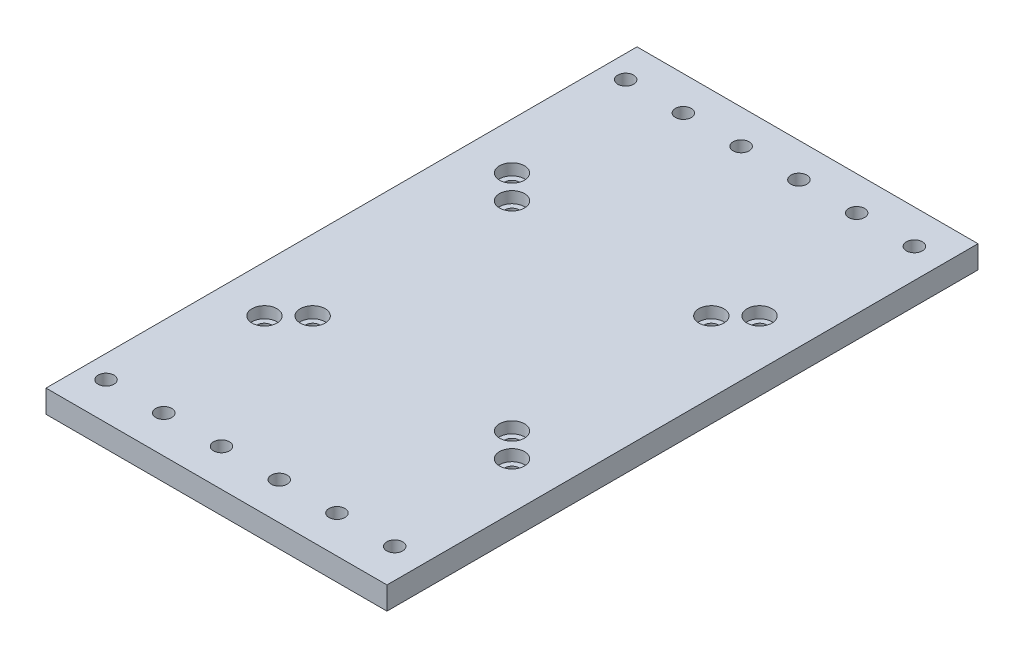
SolidWorks part; units mm, degrees
ref_plane "Front Plane" through (0, 0, 0) normal (0, 0, 1) x (1, 0, 0)
ref_plane "Top Plane" through (0, 0, 0) normal (0, 1, 0) x (1, 0, 0)
ref_plane "Right Plane" through (0, 0, 0) normal (1, 0, 0) x (0, 0, -1)
sketch "Sketch2" plane through (0, 0, 0) normal (0, 1, 0) x (1, 0, 0)
  line L1 (-75, -130) -> (75, -130)
  line L2 (-75, -130) -> (-75, 130)
  line L3 (-75, 130) -> (75, 130)
  line L4 (75, -130) -> (75, 130)
  line L5 (-75, -130) -> (75, 130) construction
  line L6 (-75, 130) -> (75, -130) construction
  point P0 (0, 0)
  dimension "D1" = 150
  dimension "D2" = 260
extrude "Boss-Extrude1" add sketch "Sketch2" along normal blind 10
sketch "Sketch3" plane through (0, 10, 0) normal (0, 1, 0) x (1, 0, 0)
  line L0 (-43.8406, -43.8406) -> (0, 0) construction
  line L1 (0, 0) -> (43.8406, 43.8406) construction
  line L2 (0, 0) -> (-14.158, -14.158) construction
  line L3 (-43.8406, 43.8406) -> (0, 0) construction
  line L4 (0, 0) -> (27.2687, 27.2687) construction
  line L5 (0, 0) -> (43.8406, -43.8406) construction
  line L6 (0, 0) -> (71.3814, -71.3814) construction
  line L7 (0, 0) -> (-73.7954, 73.7954) construction
  line L8 (-75, -130) -> (75, -130) construction
  circle A0 centre (-54.4472, -54.4472) radius 3.125
  circle A2 centre (-43.8406, -43.8406) radius 3.125
  circle A5 centre (54.4472, 54.4472) radius 3.125
  circle A6 centre (43.8406, 43.8406) radius 3.125
  circle A7 centre (-54.4472, 54.4472) radius 3.125
  circle A8 centre (-43.8406, 43.8406) radius 3.125
  circle A9 centre (54.4472, -54.4472) radius 3.125
  circle A10 centre (43.8406, -43.8406) radius 3.125
  point P21 (0, 0)
  point P25 (27.2687, 27.2687)
  dimension "D1" = 6.25
  dimension "D2" = 15
  dimension "D3" = 124
  dimension "D5" = 6.25
  dimension "D6" = 15
  dimension "D4" = 15
  dimension "D7" = 124
  dimension "D8" = 15
  dimension "D9" = 45
extrude "Cut-Extrude1" cut sketch "Sketch3" against normal through all
sketch "Sketch4" plane through (0, 10, 0) normal (0, 1, 0) x (1, 0, 0)
  circle A0 centre (-43.8406, -43.8406) radius 5.5
  circle A1 centre (-54.4472, -54.4472) radius 5.5
  circle A2 centre (43.8406, -43.8406) radius 5.5
  circle A3 centre (54.4472, -54.4472) radius 5.5
  circle A4 centre (43.8406, 43.8406) radius 5.5
  circle A5 centre (54.4472, 54.4472) radius 5.5
  circle A6 centre (-43.8406, 43.8406) radius 5.5
  circle A7 centre (-54.4472, 54.4472) radius 5.5
  dimension "D1" = 11
extrude "Cut-Extrude2" cut sketch "Sketch4" against normal mid plane 10
sketch "Sketch5" plane through (0, 10, 0) normal (0, 1, 0) x (1, 0, 0)
  line L0 (-75, 130) -> (-75, -130) construction
  line L1 (75, 130) -> (-75, 130) construction
  line L2 (-65, 115) -> (-39.6, 115) construction
  line L5 (-65, -113.6) -> (-39.6, -113.6) construction
  circle A0 centre (-65, 115) radius 3.5
  circle A1 centre (-39.6, 115) radius 3.5
  circle A2 centre (-14.2, 115) radius 3.5
  circle A3 centre (11.2, 115) radius 3.5
  circle A4 centre (36.6, 115) radius 3.5
  circle A5 centre (62, 115) radius 3.5
  circle A12 centre (-65, -113.6) radius 3.5
  circle A13 centre (-39.6, -113.6) radius 3.5
  circle A14 centre (-14.2, -113.6) radius 3.5
  circle A15 centre (11.2, -113.6) radius 3.5
  circle A16 centre (36.6, -113.6) radius 3.5
  circle A17 centre (62, -113.6) radius 3.5
  circle A18 centre (-39.6, 89.6) radius 3.5 [skipped]
  circle A19 centre (-14.2, 89.6) radius 3.5 [skipped]
  circle A20 centre (11.2, 89.6) radius 3.5 [skipped]
  circle A21 centre (36.6, 89.6) radius 3.5 [skipped]
  circle A22 centre (62, 89.6) radius 3.5 [skipped]
  circle A23 centre (-65, 89.6) radius 3.5 [skipped]
  dimension "D1" = 7
  dimension "D10" = 6
  dimension "D2" = 10
  dimension "D3" = 15
  dimension "D6" = 25.4
  dimension "D7" = 228.6
  dimension "D8" = 10
  dimension "D11" = 25.4
  dimension "D4" = 6
  dimension "D5" = 2
extrude "Cut-Extrude3" cut sketch "Sketch5" against normal through all
